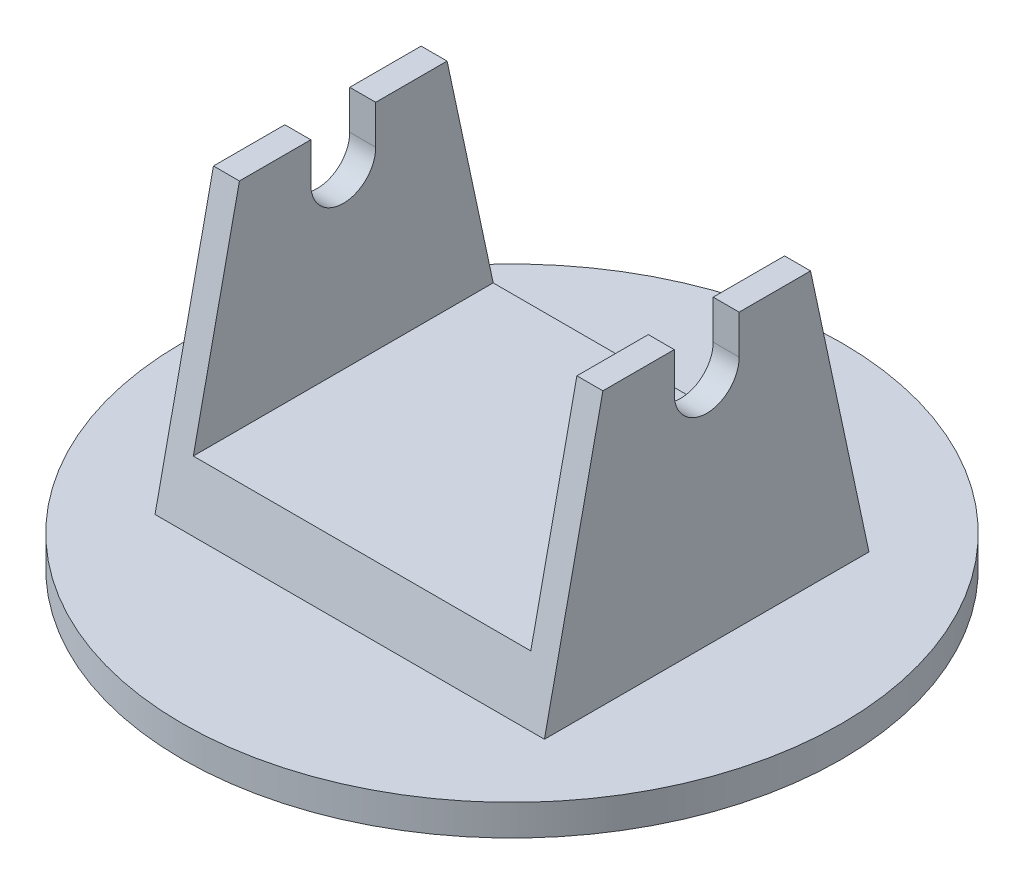
SolidWorks part; units mm, degrees
ref_plane "Front Plane" through (0, 0, 0) normal (0, 0, 1) x (1, 0, 0)
ref_plane "Top Plane" through (0, 0, 0) normal (0, 1, 0) x (1, 0, 0)
ref_plane "Right Plane" through (0, 0, 0) normal (1, 0, 0) x (0, 0, -1)
ref_plane "Plane1" through (0, 37.2625, 0) normal (0, 1, 0) x (-1, 0, 0)
sketch "Sketch2" plane through (0, 37.2625, 0) normal (0, 1, 0) x (-1, 0, 0)
  circle A0 centre (0, 0) radius 50.8
  dimension "D1" = 101.6
extrude "Boss-Extrude1" add sketch "Sketch2" along normal blind 4.7625
sketch "Sketch4" plane through (0, 0, 0) normal (1, 0, 0) x (0, 0, -1)
  line L0 (-25, 42.025) -> (25, 42.025)
  line L1 (50.8, 42.025) -> (-50.8, 42.025) construction
  line L2 (25, 42.025) -> (16, 84.025)
  line L3 (16, 84.025) -> (-16, 84.025)
  line L4 (-16, 84.025) -> (-25, 42.025)
  line L5 (0, 42.025) -> (0, 0) construction
  line L6 (0, 42.025) -> (0, 84.025) construction
  dimension "D1" = 50
  dimension "D2" = 32
  dimension "D3" = 42
extrude "Boss-Extrude2" add sketch "Sketch4" along normal mid plane 60
sketch "Sketch6" plane through (30, 0, 0) normal (1, 0, 0) x (0, 0, -1)
  line L0 (5, 78.025) -> (5, 84.025)
  line L1 (16, 84.025) -> (-16, 84.025) construction
  line L2 (-5, 78.025) -> (-5, 84.025)
  line L3 (-25, 42.025) -> (25, 42.025) construction
  line L4 (-5, 84.025) -> (5, 84.025)
  arc A0 (-5, 78.025) -> (5, 78.025) centre (0, 78.025) ccw
  dimension "D1" = 10
  dimension "D2" = 36
extrude "Cut-Extrude2" cut sketch "Sketch6" against normal through all
sketch "Sketch5" plane through (0, 0, 0) normal (0, 0, 1) x (1, 0, 0)
  line L0 (30, 84.025) -> (-30, 84.025) construction
  line L1 (-26, 50.8713) -> (26, 50.8713)
  line L2 (-26, 50.8713) -> (-26, 84.025)
  line L3 (-26, 84.025) -> (26, 84.025)
  line L4 (26, 50.8713) -> (26, 84.025)
  line L5 (-26, 50.8713) -> (26, 84.025) construction
  line L6 (-26, 84.025) -> (26, 50.8713) construction
  line L7 (30, 84.025) -> (30, 42.025) construction
  line L8 (30, 42.025) -> (-30, 42.025) construction
  point P0 (0, 67.4482)
  dimension "D1" = 4
  dimension "D2" = 8.8463
extrude "Cut-Extrude1" cut sketch "Sketch5" against normal through all and the other way through all
